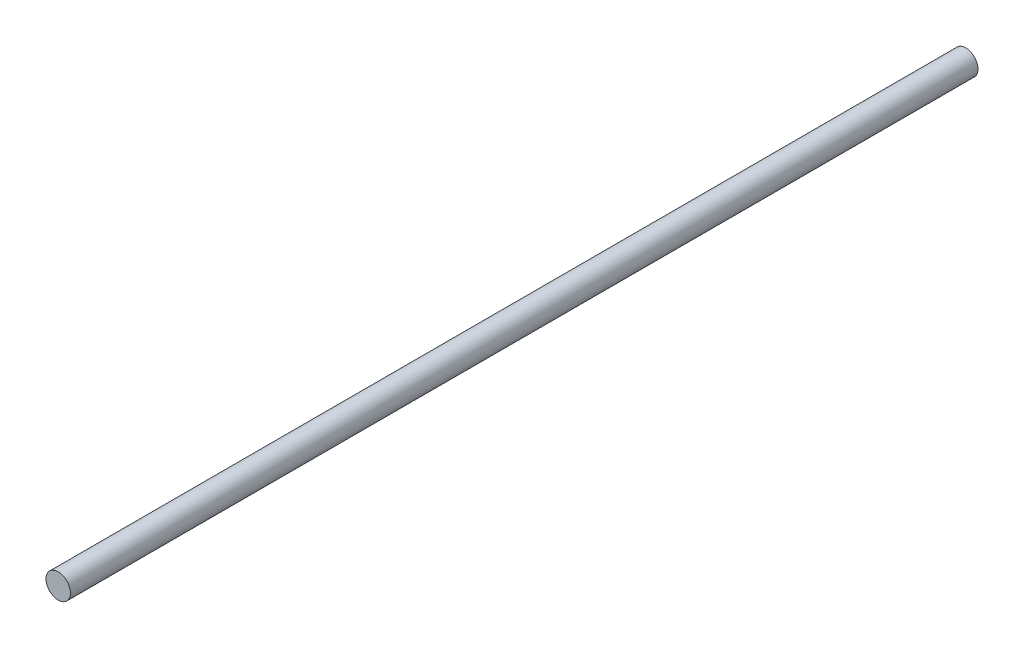
SolidWorks part; units mm, degrees
ref_plane "Front Plane" through (0, 0, 0) normal (0, 0, 1) x (1, 0, 0)
ref_plane "Top Plane" through (0, 0, 0) normal (0, 1, 0) x (1, 0, 0)
ref_plane "Right Plane" through (0, 0, 0) normal (1, 0, 0) x (0, 0, -1)
sketch "Sketch1" plane through (0, 0, 0) normal (0, 0, 1) x (1, 0, 0)
  circle A0 centre (0, 0) radius 3
extrude "Boss-Extrude2" add sketch "Sketch1" along normal blind 4.5
ref_plane "Plane2" through (0, 0, 4.5) normal (0, 0, 1) x (1, 0, 0)
sketch "Sketch3" plane through (0, 0, 4.5) normal (0, 0, 1) x (1, 0, 0)
  circle A0 centre (0, 0) radius 3
extrude "Boss-Extrude3" add sketch "Sketch3" along normal blind 201
ref_plane "Plane3" through (0, 0, 205.5) normal (0, 0, 1) x (1, 0, 0)
sketch "Sketch4" plane through (0, 0, 205.5) normal (0, 0, 1) x (1, 0, 0)
  circle A0 centre (0, 0) radius 3
extrude "Boss-Extrude4" add sketch "Sketch4" along normal blind 17
sketch "Sketch5" plane through (0, 0, 205.5) normal (0, 0, 1) x (1, 0, 0)
  circle A0 centre (0, 0) radius 3
sketch "Sketch6" plane through (0, 0, 4.5) normal (0, 0, 1) x (1, 0, 0)
  circle A0 centre (0, 0) radius 3
